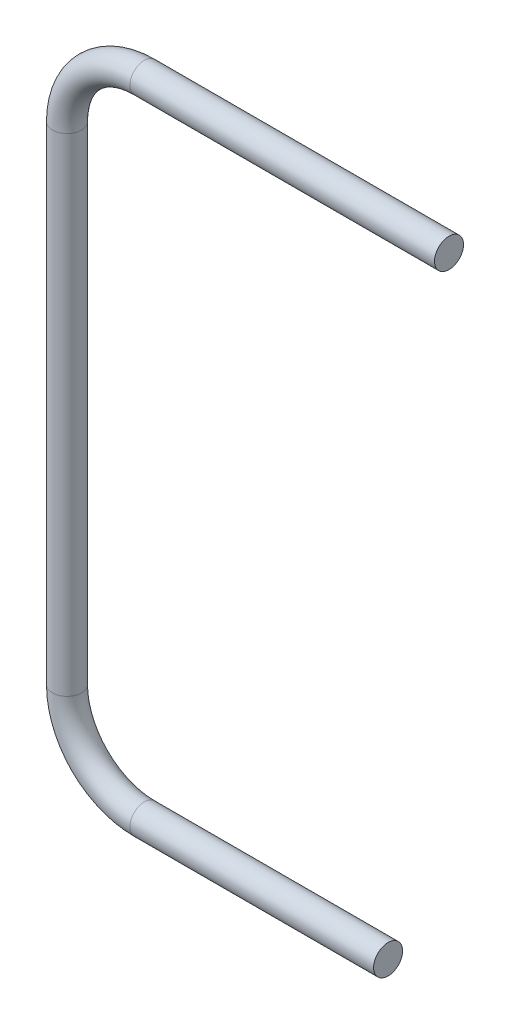
SolidWorks part; units mm, degrees
ref_plane "Front Plane" through (0, 0, 0) normal (0, 0, 1) x (1, 0, 0)
ref_plane "Top Plane" through (0, 0, 0) normal (0, 1, 0) x (1, 0, 0)
ref_plane "Right Plane" through (0, 0, 0) normal (1, 0, 0) x (0, 0, -1)
sketch "Sketch1" plane through (0, 0, 0) normal (0, 0, 1) x (1, 0, 0)
  line L0 (0, 0) -> (-40, 0)
  line L1 (-52.7, 12.7) -> (-52.7, 92.7)
  line L2 (-40, 105.4) -> (10, 105.4)
  arc A0 (-40, 0) -> (-52.7, 12.7) centre (-40, 12.7) cw
  arc A1 (-52.7, 92.7) -> (-40, 105.4) centre (-40, 92.7) cw
  dimension "D1" = 12.7
  dimension "D2" = 12.7
  dimension "D3" = 80
  dimension "D4" = 50
  dimension "D5" = 40
sweep "Sweep1" add path "Sketch1" circular profile diameter 4.7625 parameters "D3"=4.7625
